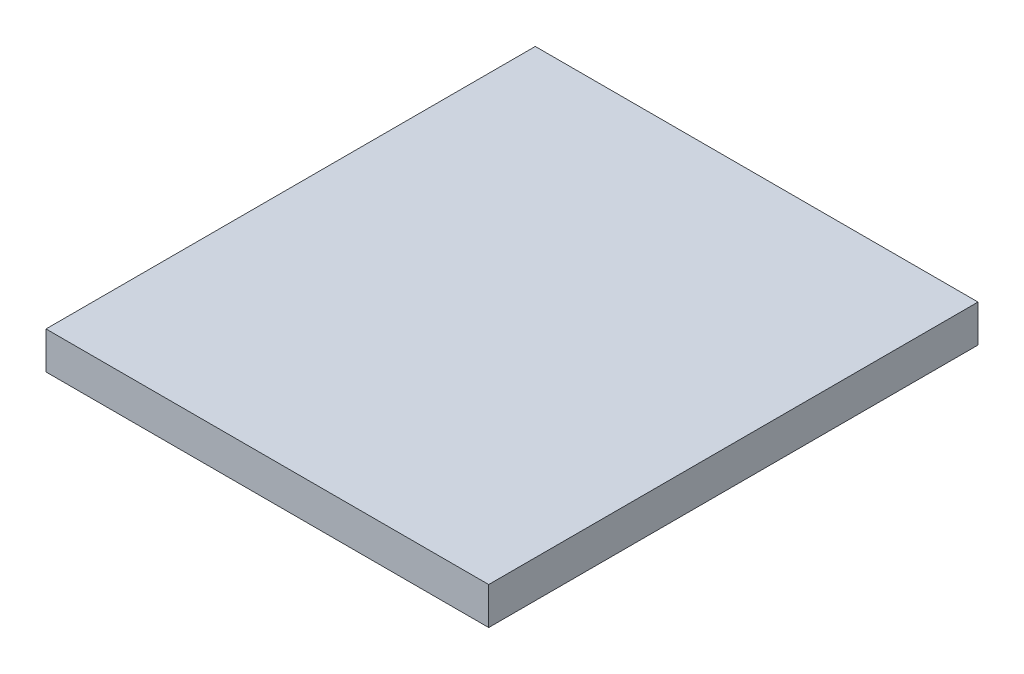
SolidWorks part; units mm, degrees
ref_plane "前视基准面" through (0, 0, 0) normal (0, 0, 1) x (1, 0, 0)
ref_plane "上视基准面" through (0, 0, 0) normal (0, 1, 0) x (1, 0, 0)
ref_plane "右视基准面" through (0, 0, 0) normal (1, 0, 0) x (0, 0, -1)
sketch "草图1" plane through (0, 0, 0) normal (0, 1, 0) x (1, 0, 0)
  line L1 (0, 0) -> (-19, 0)
  line L2 (0, 0) -> (0, 21)
  line L3 (0, 21) -> (-19, 21)
  line L4 (-19, 0) -> (-19, 21)
extrude "凸台-拉伸1" add sketch "草图1" along normal blind 1.6
